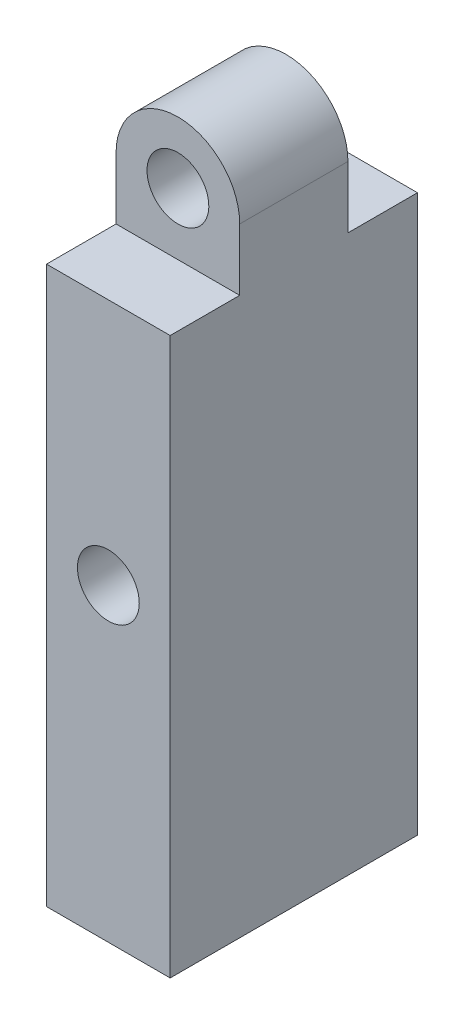
SolidWorks part; units mm, degrees
ref_plane "前视基准面" through (0, 0, 0) normal (0, 0, 1) x (1, 0, 0)
ref_plane "上视基准面" through (0, 0, 0) normal (0, 1, 0) x (1, 0, 0)
ref_plane "右视基准面" through (0, 0, 0) normal (1, 0, 0) x (0, 0, -1)
sketch "草图1" plane through (0, 0, 0) normal (0, 0, 1) x (1, 0, 0)
  line L0 (-0.2443, 7.1324) -> (-0.2443, -6.3098) construction
  line L2 (-1.2443, -4.5637) -> (-1.2443, 5.4363)
  line L4 (0.7557, -4.5637) -> (0.7557, 5.4363)
  line L5 (-1.2443, -4.5637) -> (0.7557, -4.5637)
  arc A0 (0.7557, 5.4363) -> (-1.2443, 5.4363) centre (-0.2443, 5.4363) ccw
  circle A2 centre (-0.2443, 5.4363) radius 0.5
  circle A4 centre (-0.2443, 0.4363) radius 0.5
  point P0 (0, 0)
  dimension "D2" = 1
  dimension "D3" = 1
  dimension "D6" = 1
  dimension "D5" = 10
  dimension "D7" = 5
extrude "凸台-拉伸1" add sketch "草图1" along normal blind 4
sketch "草图2" plane through (0, 0, 0) normal (1, 0, 0) x (0, 0, -1)
  line L0 (-2, 6.4363) -> (-2, 3.1839) construction
  line L1 (0, 6.4363) -> (-4, 6.4363) construction
  line L2 (-2.875, 6.4363) -> (-2.875, 4.4363)
  line L3 (-4, 4.4363) -> (-2.875, 4.4363)
  line L4 (-1.125, 4.4363) -> (-1.125, 6.4363)
  line L5 (-4, -4.5637) -> (-4, 5.4363) construction
  line L6 (0, -4.5637) -> (0, 5.4363) construction
  line L7 (0, 4.4363) -> (0, 6.4363)
  line L10 (-4, 6.4363) -> (-4, 5.4363) construction
  line L11 (-4, 6.4363) -> (-4, 4.4363)
  line L12 (-1.125, 4.4363) -> (0, 4.4363)
  line L13 (-4, 6.4363) -> (-2.875, 6.4363)
  line L14 (-1.125, 6.4363) -> (0, 6.4363)
  dimension "D1" = 1.75
  dimension "D2" = 2
extrude "切除-拉伸2" cut sketch "草图2" against normal through all both and the other way through all
